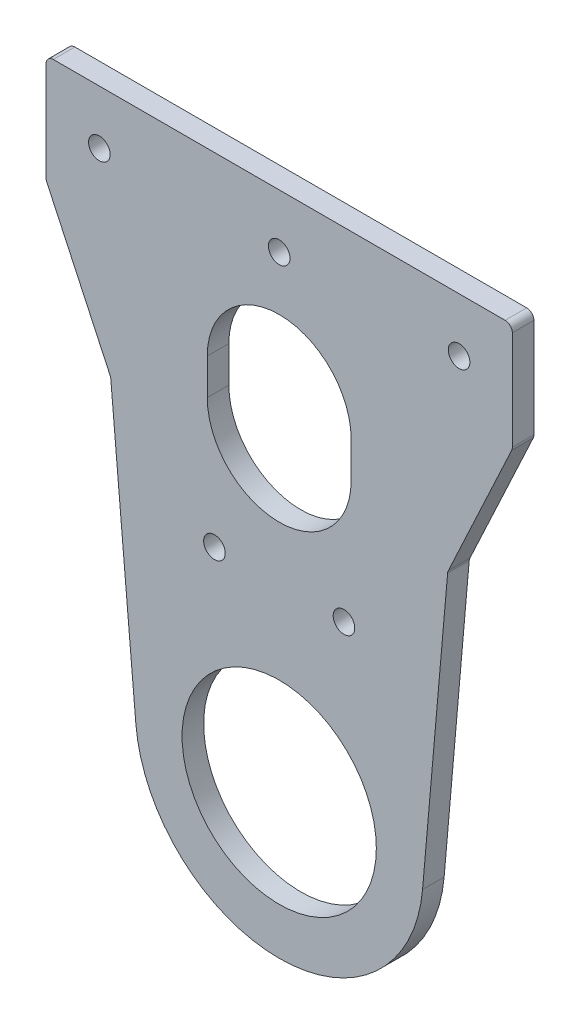
SolidWorks part; units mm, degrees
material "Thornel Mat VMA"
ref_plane "前视基准面" through (0, 0, 0) normal (0, 0, 1) x (1, 0, 0)
ref_plane "上视基准面" through (0, 0, 0) normal (0, 1, 0) x (1, 0, 0)
ref_plane "右视基准面" through (0, 0, 0) normal (1, 0, 0) x (0, 0, -1)
sketch "草图1" plane through (0, 0, 0) normal (0, 0, 1) x (1, 0, 0)
  line L0 (0, 0) -> (0, 65) construction
  line L1 (-25, 65) -> (25, 65) construction
  line L2 (-32.4, 72.5) -> (32.4, 72.5)
  line L3 (32.4, 72.5) -> (32.4, 57.5)
  line L5 (32.4, 57.5) -> (23.4227, 38.248)
  line L6 (23.4227, 38.248) -> (19.9239, -1.7431)
  line L7 (-32.4, 72.5) -> (-32.4, 57.5)
  line L9 (-32.4, 57.5) -> (-23.4227, 38.248)
  line L10 (-23.4227, 38.248) -> (-19.9239, -1.7431)
  line L11 (0, 47.5) -> (0, 42.5) construction
  line L12 (10, 47.5) -> (10, 42.5)
  line L13 (-10, 47.5) -> (-10, 42.5)
  arc A0 (-19.9239, -1.7431) -> (19.9239, -1.7431) centre (0, 0) ccw
  circle A1 centre (25, 65) radius 1.5
  circle A2 centre (-25, 65) radius 1.5
  circle A3 centre (0, 65) radius 1.5
  circle A4 centre (0, 0) radius 13.5
  arc A5 (10, 47.5) -> (-10, 47.5) centre (0, 47.5) ccw
  arc A6 (-10, 42.5) -> (10, 42.5) centre (0, 42.5) ccw
  circle A7 centre (-9, 25) radius 1.5
  circle A8 centre (9, 25) radius 1.5
  point P19 (0, 72.5)
  point P20 (32.4, 65)
  point P23 (0, 45)
  dimension "D1" = 3
  dimension "D2" = 50
  dimension "D4" = 40
  dimension "D10" = 27
  dimension "D11" = 10
  dimension "D14" = 3
  dimension "D15" = 18
  dimension "D16" = 25
  dimension "D3" = 65
  dimension "D5" = 15
  dimension "D6" = 64.8
  dimension "D7" = 17.5
  dimension "D8" = 50
  dimension "D9" = 10
  dimension "D12" = 5
extrude "凸台-拉伸1" add sketch "草图1" along normal blind 3
fillet "圆角2" radius 1 6 edges at (32.4, 72.5, 1.5) (23.4227, 38.248, 1.5) (-32.4, 72.5, 1.5) (-23.4227, 38.248, 1.5) (-32.4, 57.5, 1.5) (32.4, 57.5, 1.5)
